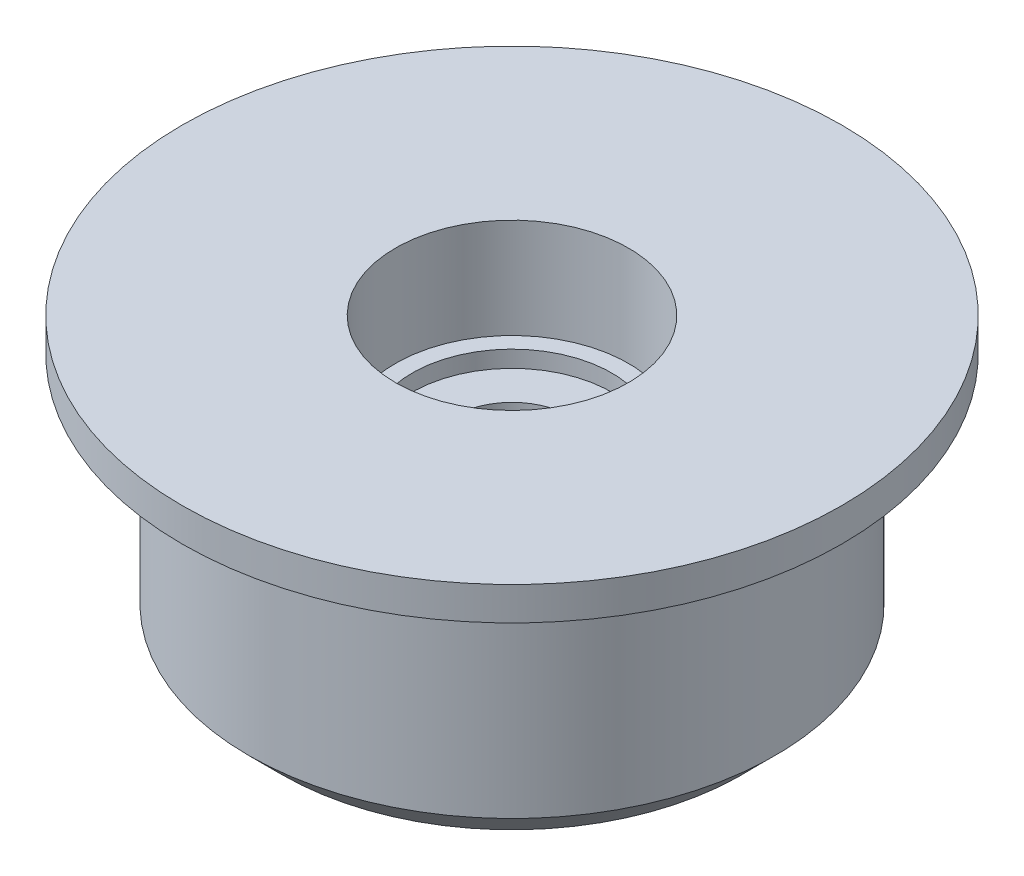
SolidWorks part; units mm, degrees
ref_plane "Front Plane" through (0, 0, 0) normal (0, 0, 1) x (1, 0, 0)
ref_plane "Top Plane" through (0, 0, 0) normal (0, 1, 0) x (1, 0, 0)
ref_plane "Right Plane" through (0, 0, 0) normal (1, 0, 0) x (0, 0, -1)
sketch "Sketch1" plane through (0, 0, 0) normal (0, 0, 1) x (1, 0, 0)
  line L0 (1.75, 0) -> (7.9, 0)
  line L1 (3.5, 8.5) -> (9.9, 8.5)
  line L2 (9.9, 8.5) -> (9.9, 7.5)
  line L3 (9.9, 7.5) -> (7.9, 7.5)
  line L4 (7.9, 7.5) -> (7.9, 0)
  line L7 (3.5, 8.5) -> (3.5, 5.5)
  line L8 (3.5, 5.5) -> (3, 5.5)
  line L9 (3, 5.5) -> (3, 5)
  line L10 (3, 5) -> (1.75, 5)
  line L11 (1.75, 5) -> (1.75, 0)
  point P0 (1.75, 2.5)
  dimension "D2" = 1
  dimension "D3" = 1.75
  dimension "D4" = 0.5
  dimension "D5" = 0.5
  dimension "D6" = 2
  dimension "D7" = 3
  dimension "D9" = 5
  dimension "D12" = 7.9
  dimension "D13" = 3.5
ref_axis "Axis1" through (0, 37.275, 0) along (0, -1, 0)
revolve "Revolve1" add sketch "Sketch1" angle 360 about axis through (0, 37.275, 0) along (0, -1, 0)
chamfer "Chamfer1" distance 1 angle 45 1 edges at (0, 0, 7.9)
